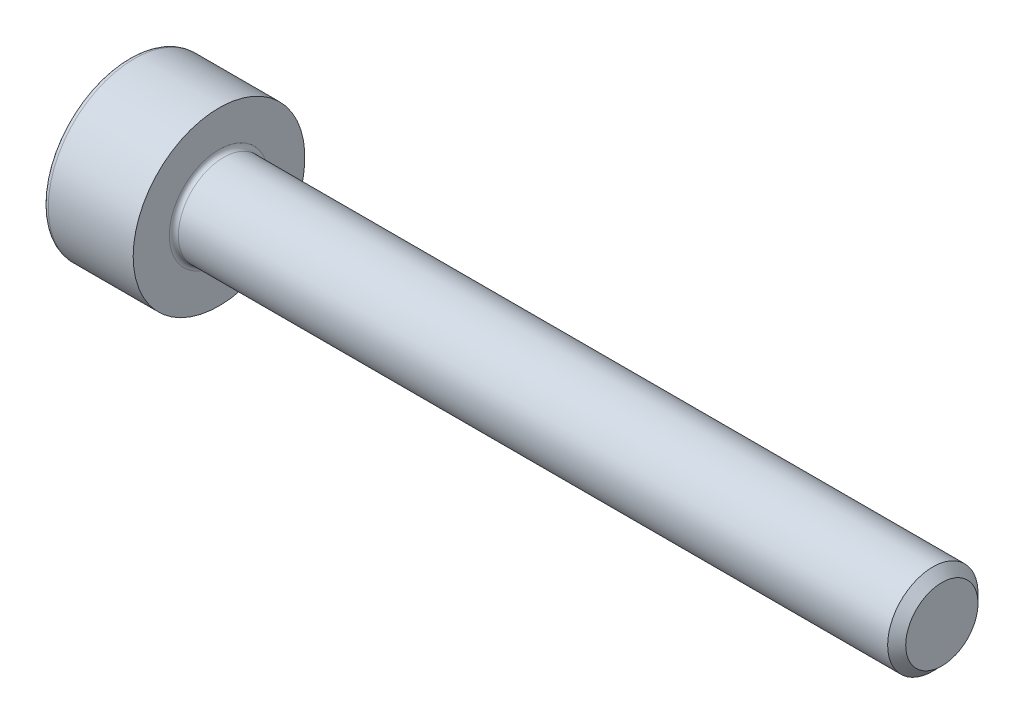
SolidWorks part; units mm, degrees
ref_plane "Front Plane" through (0, 0, 0) normal (0, 0, 1) x (1, 0, 0)
ref_plane "Top Plane" through (0, 0, 0) normal (0, 1, 0) x (1, 0, 0)
ref_plane "Right Plane" through (0, 0, 0) normal (1, 0, 0) x (0, 0, -1)
sketch "Sketch1" plane through (0, 0, 0) normal (0, 0, 1) x (1, 0, 0)
  line L0 (0, 0) -> (0, 1.9)
  line L1 (0, 1.9) -> (2, 1.9)
  line L2 (2, 1.9) -> (2, 0)
  line L3 (0, 0) -> (4.2799, 0) construction
  line L4 (2, 0) -> (18, 0)
  line L5 (18, 0) -> (18, 1)
  line L6 (18, 1) -> (2, 1)
  dimension "D1" = 16
revolve "Revolve1" add sketch "Sketch1" angle 360 about L3
fillet "Fillet1" radius 0.1 1 edges at (2, 0, 1)
fillet "Fillet2" radius 0.12 1 edges at (0, 0, 1.9)
chamfer "Chamfer1" distance 0.2 angle 45 1 edges at (18, 0, 1)
sketch "Sketch2" plane through (0, 0, 0) normal (-1, 0, 0) x (0, 0, 1)
  line L1 (0, 0.866) -> (-0.75, 0.433)
  line L2 (-0.75, 0.433) -> (-0.75, -0.433)
  line L3 (-0.75, -0.433) -> (0, -0.866)
  line L4 (0, -0.866) -> (0.75, -0.433)
  line L5 (0.75, -0.433) -> (0.75, 0.433)
  line L6 (0.75, 0.433) -> (0, 0.866)
  circle A0 centre (0, 0) radius 0.75 construction
extrude "Extrude1" cut sketch "Sketch2" against normal blind 1
